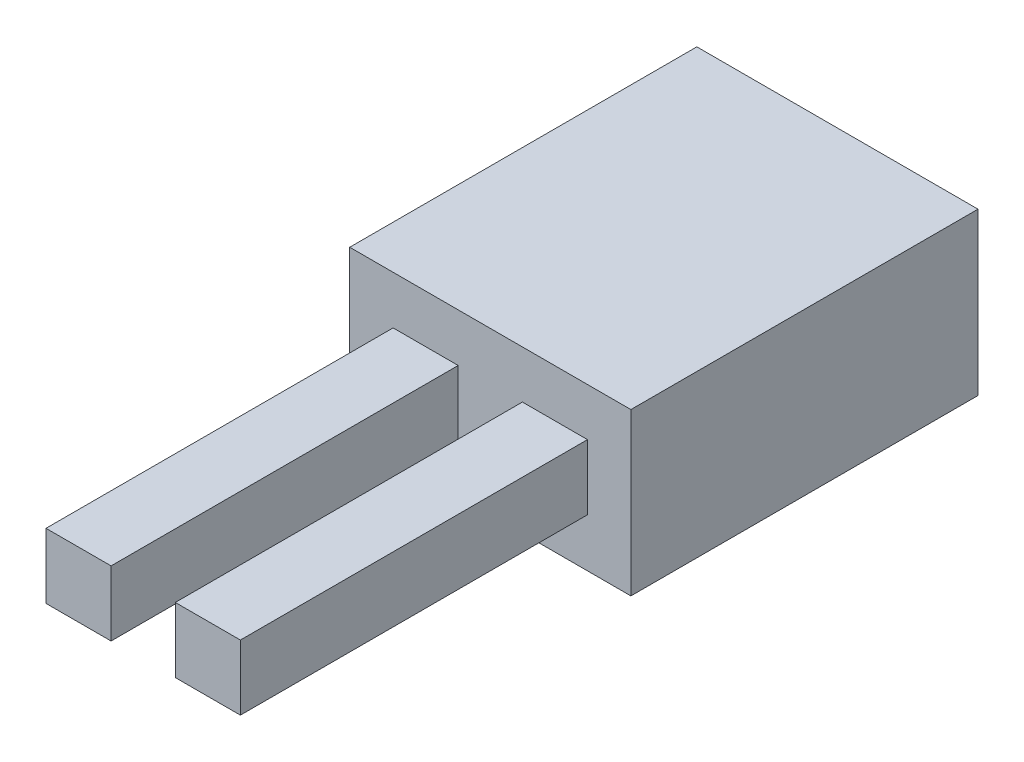
SolidWorks part; units mm, degrees
ref_plane "Front Plane" through (0, 0, 0) normal (0, 0, 1) x (1, 0, 0)
ref_plane "Top Plane" through (0, 0, 0) normal (0, 1, 0) x (1, 0, 0)
ref_plane "Right Plane" through (0, 0, 0) normal (1, 0, 0) x (0, 0, -1)
sketch "Sketch1" plane through (0, 0, 0) normal (0, 1, 0) x (1, 0, 0)
  line L1 (0, 0) -> (3.24, 0)
  line L2 (0, 0) -> (0, 4)
  line L3 (0, 4) -> (3.24, 4)
  line L4 (3.24, 0) -> (3.24, 4)
  dimension "D1" = 3.24
  dimension "D2" = 4
extrude "Boss-Extrude1" add sketch "Sketch1" along normal blind 1.86
sketch "Sketch2" plane through (0, 0, 0) normal (0, 0, 1) x (1, 0, 0)
  line L0 (0, 0) -> (3.24, 0) construction
  line L1 (0.5, 1.305) -> (1.25, 1.305)
  line L2 (0.5, 1.305) -> (0.5, 0.555)
  line L3 (0.5, 0.555) -> (1.25, 0.555)
  line L4 (1.25, 1.305) -> (1.25, 0.555)
  line L5 (1.99, 1.31) -> (2.74, 1.31)
  line L6 (1.99, 1.31) -> (1.99, 0.56)
  line L7 (1.99, 0.56) -> (2.74, 0.56)
  line L8 (2.74, 1.31) -> (2.74, 0.56)
  line L9 (0, 1.86) -> (3.24, 1.86) construction
  line L10 (0, 1.86) -> (0, 0) construction
  line L11 (3.24, 1.86) -> (3.24, 0) construction
  dimension "D1" = 0.75
  dimension "D2" = 0.75
  dimension "D3" = 0.75
  dimension "D4" = 0.75
  dimension "D5" = 0.555
  dimension "D6" = 0.555
  dimension "D7" = 0.56
  dimension "D8" = 0.5
  dimension "D9" = 0.5
extrude "Boss-Extrude2" add sketch "Sketch2" along normal blind 4
